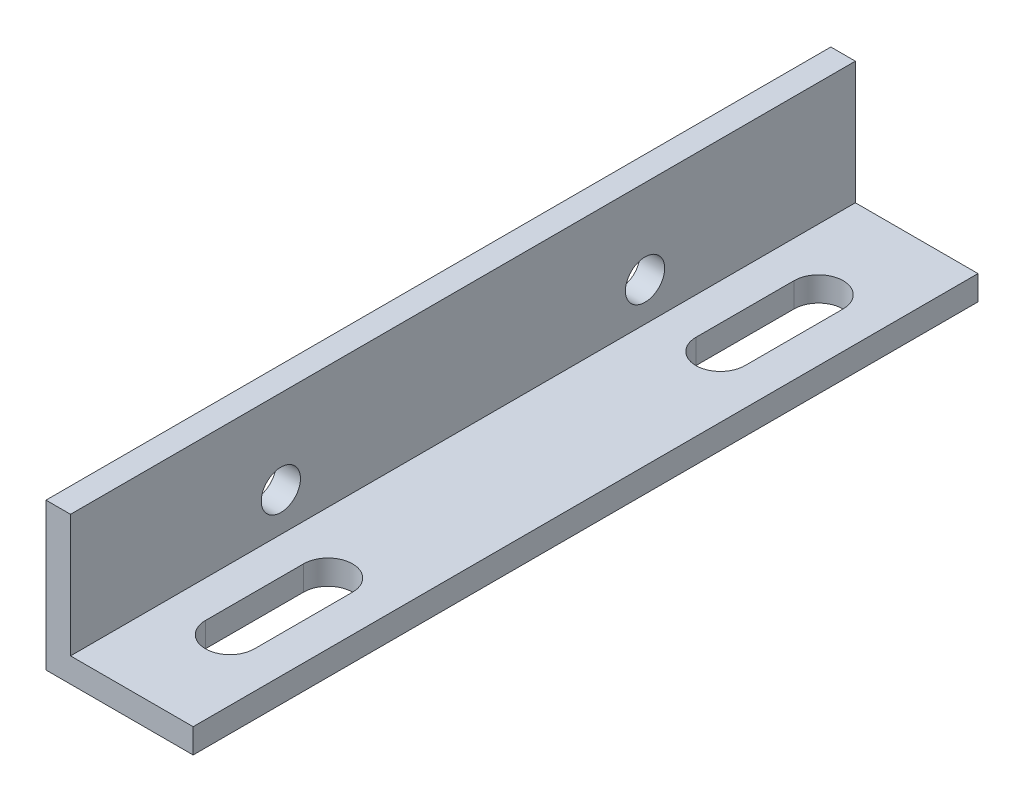
SolidWorks part; units mm, degrees
ref_plane "Front Plane" through (0, 0, 0) normal (0, 0, 1) x (1, 0, 0)
ref_plane "Top Plane" through (0, 0, 0) normal (0, 1, 0) x (1, 0, 0)
ref_plane "Right Plane" through (0, 0, 0) normal (1, 0, 0) x (0, 0, -1)
sketch "Sketch1" plane through (0, 0, 3.1467) normal (0, 0, 1) x (1, 0, 0)
  line L0 (21.463, 31.75) -> (21.463, 12.7)
  line L1 (21.463, 28.4226) -> (21.463, 60.4774) construction
  line L2 (21.463, 12.7) -> (40.513, 12.7)
  line L3 (-127, 12.7) -> (127, 12.7) construction
  line L4 (40.513, 12.7) -> (40.513, 15.875)
  line L5 (40.513, 15.875) -> (24.638, 15.875)
  line L6 (24.638, 15.875) -> (24.638, 31.75)
  line L7 (24.638, 31.75) -> (21.463, 31.75)
  dimension "D1" = 19.05
  dimension "D2" = 3.175
extrude "Extrude1" add sketch "Sketch1" along normal mid plane 101.6
sketch "Sketch3" plane through (0, 15.875, 0) normal (0, 1, 0) x (-1, 0, 0)
  line L0 (-21.463, 3.1467) -> (-57.1682, 3.1467) construction
  line L1 (-21.463, 53.9467) -> (-21.463, -47.6533) construction
  line L2 (-40.513, -47.6533) -> (-24.638, -47.6533) construction
  line L3 (-35.7505, -34.9533) -> (-35.7505, -22.2533)
  line L4 (-29.4005, -34.9533) -> (-29.4005, -22.2533)
  line L5 (-29.4005, 41.2467) -> (-29.4005, 28.5467)
  line L6 (-35.7505, 41.2467) -> (-35.7505, 28.5467)
  arc A0 (-35.7505, -34.9533) -> (-29.4005, -34.9533) centre (-32.5755, -34.9533) ccw
  arc A1 (-29.4005, -22.2533) -> (-35.7505, -22.2533) centre (-32.5755, -22.2533) ccw
  arc A2 (-29.4005, 28.5467) -> (-35.7505, 28.5467) centre (-32.5755, 28.5467) cw
  arc A3 (-35.7505, 41.2467) -> (-29.4005, 41.2467) centre (-32.5755, 41.2467) cw
  point P10 (-32.5755, -47.6533)
  dimension "D1" = 6.35
  dimension "D2" = 38.1
  dimension "D3" = 12.7
extrude "Cut-Extrude1" cut sketch "Sketch3" against normal through all
sketch "Sketch4" plane through (24.638, 0, 0) normal (1, 0, 0) x (0, 0, -1)
  circle A0 centre (20.4245, 20.8788) radius 2.54 construction
  circle A1 centre (20.4245, 20.8788) radius 2.54
  circle A2 centre (-26.7179, 20.8788) radius 2.54 construction
  circle A3 centre (-26.7179, 20.8788) radius 2.54
extrude "Cut-Extrude2" cut sketch "Sketch4" against normal through all
